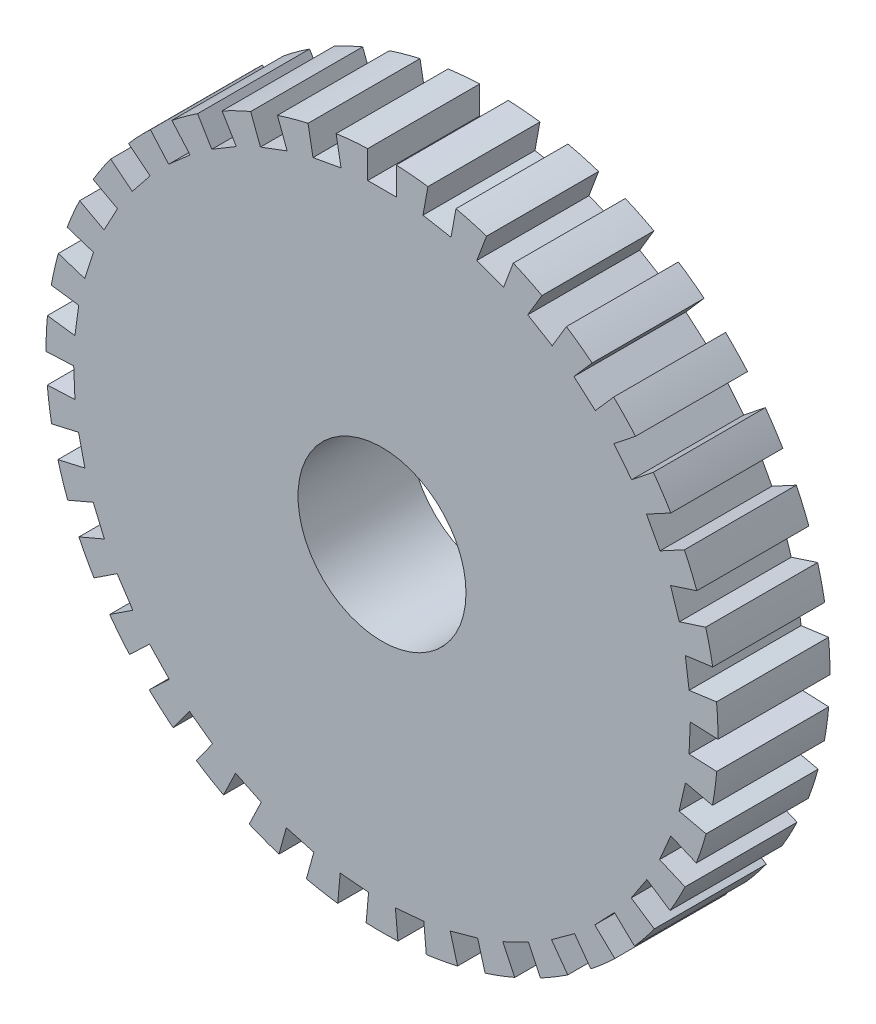
SolidWorks part; units mm, degrees
ref_plane "Front Plane" through (0, 0, 0) normal (0, 0, 1) x (1, 0, 0)
ref_plane "Top Plane" through (0, 0, 0) normal (0, 1, 0) x (1, 0, 0)
ref_plane "Right Plane" through (0, 0, 0) normal (1, 0, 0) x (0, 0, -1)
sketch "Sketch1" plane through (0, 0, 0) normal (0, 0, 1) x (1, 0, 0)
  circle A1 centre (0, 0) radius 6
extrude "Boss-Extrude1" add sketch "Sketch1" along normal blind 2
sketch "Sketch2" plane through (0, 0, 2) normal (0, 0, 1) x (1, 0, 0)
  line L0 (-0.2547, 5.5) -> (-0.2547, 6.1675)
  line L1 (-0.2547, 5.5) -> (0.2547, 5.5)
  line L2 (1.2326, 5.3661) -> (1.3518, 6.0229)
  line L3 (-0.2547, 6.1675) -> (0.2547, 6.1675)
  line L4 (0.2547, 5.5) -> (0.2547, 6.1675)
  line L5 (0.8507, 6.1138) -> (1.3518, 6.0229)
  line L6 (0.7315, 5.4571) -> (0.8507, 6.1138)
  line L7 (0.7315, 5.4571) -> (1.2326, 5.3661)
  line L8 (2.171, 5.0598) -> (2.4055, 5.6847)
  line L9 (1.9287, 5.8637) -> (2.4055, 5.6847)
  line L10 (1.6941, 5.2388) -> (1.9287, 5.8637)
  line L11 (1.6941, 5.2388) -> (2.171, 5.0598)
  line L12 (3.0396, 4.5909) -> (3.3819, 5.1638)
  line L13 (2.9447, 5.4251) -> (3.3819, 5.1638)
  line L14 (2.6023, 4.8521) -> (2.9447, 5.4251)
  line L15 (2.6023, 4.8521) -> (3.0396, 4.5909)
  line L16 (3.8104, 3.9743) -> (4.2496, 4.477)
  line L17 (3.866, 4.8121) -> (4.2496, 4.477)
  line L18 (3.4269, 4.3094) -> (3.866, 4.8121)
  line L19 (3.4269, 4.3094) -> (3.8104, 3.9743)
  line L20 (4.4589, 3.2301) -> (4.9807, 3.6463)
  line L21 (4.6631, 4.0445) -> (4.9807, 3.6463)
  line L22 (4.1413, 3.6283) -> (4.6631, 4.0445)
  line L23 (4.1413, 3.6283) -> (4.4589, 3.2301)
  line L24 (4.964, 2.382) -> (5.5517, 2.6983)
  line L25 (5.3104, 3.1468) -> (5.5517, 2.6983)
  line L26 (4.7226, 2.8305) -> (5.3104, 3.1468)
  line L27 (4.7226, 2.8305) -> (4.964, 2.382)
  line L28 (5.3095, 1.4574) -> (5.9443, 1.6637)
  line L29 (5.7869, 2.1481) -> (5.9443, 1.6637)
  line L30 (5.1521, 1.9418) -> (5.7869, 2.1481)
  line L31 (5.1521, 1.9418) -> (5.3095, 1.4574)
  line L32 (5.4844, 0.4859) -> (6.1458, 0.5755)
  line L33 (6.0775, 1.0802) -> (6.1458, 0.5755)
  line L34 (5.416, 0.9906) -> (6.0775, 1.0802)
  line L35 (5.416, 0.9906) -> (5.4844, 0.4859)
  line L36 (5.483, -0.5012) -> (6.1498, -0.5311)
  line L37 (6.1727, -0.0223) -> (6.1498, -0.5311)
  line L38 (5.5059, 0.0076) -> (6.1727, -0.0223)
  line L39 (5.5059, 0.0076) -> (5.483, -0.5012)
  line L40 (5.3054, -1.4721) -> (5.9562, -1.6207)
  line L41 (6.0695, -1.1241) -> (5.9562, -1.6207)
  line L42 (5.4188, -0.9756) -> (6.0695, -1.1241)
  line L43 (5.4188, -0.9756) -> (5.3054, -1.4721)
  line L44 (4.9573, -2.3958) -> (5.5711, -2.6581)
  line L45 (5.7713, -2.1898) -> (5.5711, -2.6581)
  line L46 (5.1575, -1.9275) -> (5.7713, -2.1898)
  line L47 (5.1575, -1.9275) -> (4.9573, -2.3958)
  line L48 (4.4499, -3.2425) -> (5.0069, -3.6102)
  line L49 (5.2875, -3.1851) -> (5.0069, -3.6102)
  line L50 (4.7304, -2.8174) -> (5.2875, -3.1851)
  line L51 (4.7304, -2.8174) -> (4.4499, -3.2425)
  line L52 (3.7994, -3.9849) -> (4.2818, -4.4462)
  line L53 (4.6338, -4.078) -> (4.2818, -4.4462)
  line L54 (4.1514, -3.6168) -> (4.6338, -4.078)
  line L55 (4.1514, -3.6168) -> (3.7994, -3.9849)
  line L56 (3.0268, -4.5993) -> (3.4191, -5.1393)
  line L57 (3.8312, -4.8399) -> (3.4191, -5.1393)
  line L58 (3.4388, -4.2999) -> (3.8312, -4.8399)
  line L59 (3.4388, -4.2999) -> (3.0268, -4.5993)
  line L60 (2.1569, -5.0658) -> (2.4465, -5.6672)
  line L61 (2.9054, -5.4462) -> (2.4465, -5.6672)
  line L62 (2.6158, -4.8448) -> (2.9054, -5.4462)
  line L63 (2.6158, -4.8448) -> (2.1569, -5.0658)
  line L64 (1.2177, -5.3695) -> (1.3953, -6.013)
  line L65 (1.8863, -5.8775) -> (1.3953, -6.013)
  line L66 (1.7087, -5.234) -> (1.8863, -5.8775)
  line L67 (1.7087, -5.234) -> (1.2177, -5.3695)
  line L68 (0.2394, -5.5007) -> (0.2992, -6.1655)
  line L69 (0.8065, -6.1198) -> (0.2992, -6.1655)
  line L70 (0.7467, -5.455) -> (0.8065, -6.1198)
  line L71 (0.7467, -5.455) -> (0.2394, -5.5007)
  line L72 (-0.7467, -5.455) -> (-0.8065, -6.1198)
  line L73 (-0.2992, -6.1655) -> (-0.8065, -6.1198)
  line L74 (-0.2394, -5.5007) -> (-0.2992, -6.1655)
  line L75 (-0.2394, -5.5007) -> (-0.7467, -5.455)
  line L76 (-1.7087, -5.234) -> (-1.8863, -5.8775)
  line L77 (-1.3953, -6.013) -> (-1.8863, -5.8775)
  line L78 (-1.2177, -5.3695) -> (-1.3953, -6.013)
  line L79 (-1.2177, -5.3695) -> (-1.7087, -5.234)
  line L80 (-2.6158, -4.8448) -> (-2.9054, -5.4462)
  line L81 (-2.4465, -5.6672) -> (-2.9054, -5.4462)
  line L82 (-2.1569, -5.0658) -> (-2.4465, -5.6672)
  line L83 (-2.1569, -5.0658) -> (-2.6158, -4.8448)
  line L84 (-3.4388, -4.2999) -> (-3.8312, -4.8399)
  line L85 (-3.4191, -5.1393) -> (-3.8312, -4.8399)
  line L86 (-3.0268, -4.5993) -> (-3.4191, -5.1393)
  line L87 (-3.0268, -4.5993) -> (-3.4388, -4.2999)
  line L88 (-4.1514, -3.6168) -> (-4.6338, -4.078)
  line L89 (-4.2818, -4.4462) -> (-4.6338, -4.078)
  line L90 (-3.7994, -3.9849) -> (-4.2818, -4.4462)
  line L91 (-3.7994, -3.9849) -> (-4.1514, -3.6168)
  line L92 (-4.7304, -2.8174) -> (-5.2875, -3.1851)
  line L93 (-5.0069, -3.6102) -> (-5.2875, -3.1851)
  line L94 (-4.4499, -3.2425) -> (-5.0069, -3.6102)
  line L95 (-4.4499, -3.2425) -> (-4.7304, -2.8174)
  line L96 (-5.1575, -1.9275) -> (-5.7713, -2.1898)
  line L97 (-5.5711, -2.6581) -> (-5.7713, -2.1898)
  line L98 (-4.9573, -2.3958) -> (-5.5711, -2.6581)
  line L99 (-4.9573, -2.3958) -> (-5.1575, -1.9275)
  line L100 (-5.4188, -0.9756) -> (-6.0695, -1.1241)
  line L101 (-5.9562, -1.6207) -> (-6.0695, -1.1241)
  line L102 (-5.3054, -1.4721) -> (-5.9562, -1.6207)
  line L103 (-5.3054, -1.4721) -> (-5.4188, -0.9756)
  line L104 (-5.5059, 0.0076) -> (-6.1727, -0.0223)
  line L105 (-6.1498, -0.5311) -> (-6.1727, -0.0223)
  line L106 (-5.483, -0.5012) -> (-6.1498, -0.5311)
  line L107 (-5.483, -0.5012) -> (-5.5059, 0.0076)
  line L108 (-5.416, 0.9906) -> (-6.0775, 1.0802)
  line L109 (-6.1458, 0.5755) -> (-6.0775, 1.0802)
  line L110 (-5.4844, 0.4859) -> (-6.1458, 0.5755)
  line L111 (-5.4844, 0.4859) -> (-5.416, 0.9906)
  line L112 (-5.1521, 1.9418) -> (-5.7869, 2.1481)
  line L113 (-5.9443, 1.6637) -> (-5.7869, 2.1481)
  line L114 (-5.3095, 1.4574) -> (-5.9443, 1.6637)
  line L115 (-5.3095, 1.4574) -> (-5.1521, 1.9418)
  line L116 (-4.7226, 2.8305) -> (-5.3104, 3.1468)
  line L117 (-5.5517, 2.6983) -> (-5.3104, 3.1468)
  line L118 (-4.964, 2.382) -> (-5.5517, 2.6983)
  line L119 (-4.964, 2.382) -> (-4.7226, 2.8305)
  line L120 (-4.1413, 3.6283) -> (-4.6631, 4.0445)
  line L121 (-4.9807, 3.6463) -> (-4.6631, 4.0445)
  line L122 (-4.4589, 3.2301) -> (-4.9807, 3.6463)
  line L123 (-4.4589, 3.2301) -> (-4.1413, 3.6283)
  line L124 (-3.4269, 4.3094) -> (-3.866, 4.8121)
  line L125 (-4.2496, 4.477) -> (-3.866, 4.8121)
  line L126 (-3.8104, 3.9743) -> (-4.2496, 4.477)
  line L127 (-3.8104, 3.9743) -> (-3.4269, 4.3094)
  line L128 (-2.6023, 4.8521) -> (-2.9447, 5.4251)
  line L129 (-3.3819, 5.1638) -> (-2.9447, 5.4251)
  line L130 (-3.0396, 4.5909) -> (-3.3819, 5.1638)
  line L131 (-3.0396, 4.5909) -> (-2.6023, 4.8521)
  line L132 (-1.6941, 5.2388) -> (-1.9287, 5.8637)
  line L133 (-2.4055, 5.6847) -> (-1.9287, 5.8637)
  line L134 (-2.171, 5.0598) -> (-2.4055, 5.6847)
  line L135 (-2.171, 5.0598) -> (-1.6941, 5.2388)
  line L136 (-0.7315, 5.4571) -> (-0.8507, 6.1138)
  line L137 (-1.3518, 6.0229) -> (-0.8507, 6.1138)
  line L138 (-1.2326, 5.3661) -> (-1.3518, 6.0229)
  line L139 (-1.2326, 5.3661) -> (-0.7315, 5.4571)
  point P145 (0, 0)
  dimension "D1" = 35
extrude "Cut-Extrude3" cut sketch "Sketch2" against normal blind 2
sketch "Sketch3" plane through (0, 0, 2) normal (0, 0, 1) x (1, 0, 0)
  circle A0 centre (0, 0) radius 1.5
extrude "Cut-Extrude4" cut sketch "Sketch3" against normal blind 2
